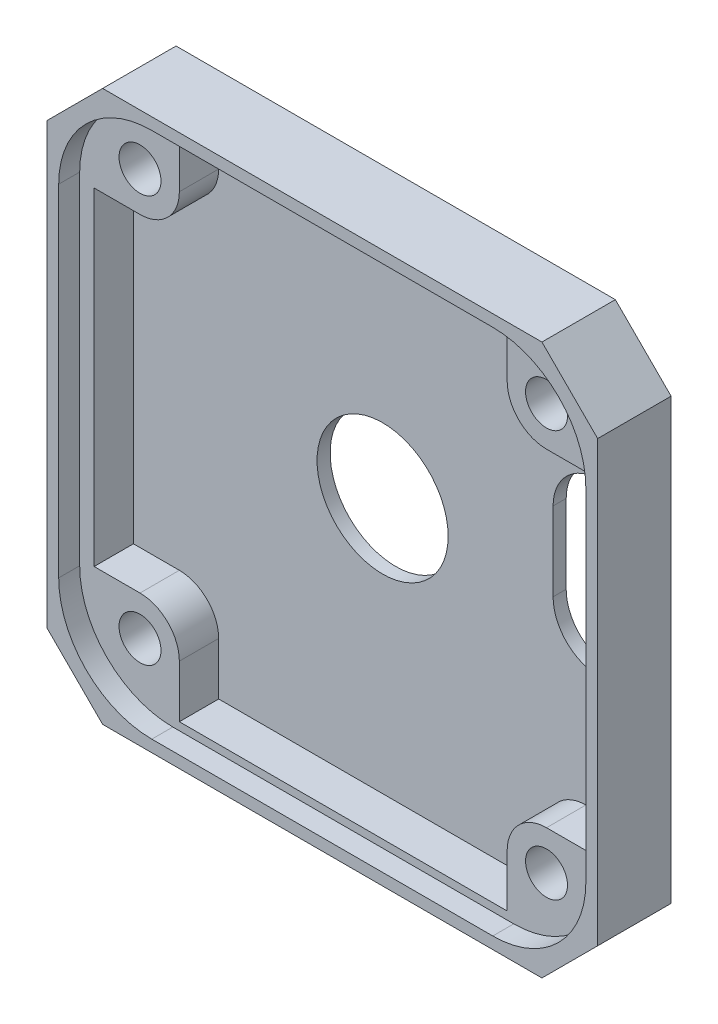
SolidWorks part; units mm, degrees
ref_plane "前视基准面" through (0, 0, 0) normal (0, 0, 1) x (1, 0, 0)
ref_plane "上视基准面" through (0, 0, 0) normal (0, 1, 0) x (1, 0, 0)
ref_plane "右视基准面" through (0, 0, 0) normal (1, 0, 0) x (0, 0, -1)
sketch "草图1" plane through (0, 0, 0) normal (0, 0, 1) x (1, 0, 0)
  line L0 (-21, 16.75) -> (-21, -16.75)
  line L1 (-16.75, 21) -> (16.75, 21)
  line L2 (-21, 16.75) -> (-16.75, 21)
  line L3 (21, 16.75) -> (21, -16.75)
  line L4 (-16.75, -21) -> (16.75, -21)
  line L5 (16.75, 21) -> (21, 16.75)
  line L6 (21, -16.75) -> (16.75, -21)
  line L7 (-21, -16.75) -> (-16.75, -21)
  line L12 (13, 6) -> (13, 0)
  line L15 (16.5, 9.5) -> (20, 9.5)
  line L16 (16.5, -3.5) -> (20, -3.5)
  line L17 (20, 9.5) -> (20, -3.5)
  circle A4 centre (0, 0) radius 5
  circle A7 centre (-15.5, 15.5) radius 1.6
  circle A8 centre (15.5, 15.5) radius 1.6
  circle A9 centre (-15.5, -15.5) radius 1.6
  circle A10 centre (15.5, -15.5) radius 1.6
  arc A11 (13, 0) -> (16.5, -3.5) centre (16.5, 0) ccw
  arc A12 (16.5, 9.5) -> (13, 6) centre (16.5, 6) ccw
extrude "凸台-拉伸3" add sketch "草图1" along normal blind 1
sketch "草图3" plane through (0, 0, 1) normal (0, 0, 1) x (1, 0, 0)
  line L0 (-16.75, 21) -> (-21, 16.75)
  line L1 (-21, 16.75) -> (-21, -16.75)
  line L2 (-21, -16.75) -> (-16.75, -21)
  line L3 (-16.75, -21) -> (16.75, -21)
  line L4 (16.75, -21) -> (21, -16.75)
  line L5 (21, -16.75) -> (21, 16.75)
  line L6 (21, 16.75) -> (16.75, 21)
  line L7 (16.75, 21) -> (-16.75, 21)
  line L8 (-12.5, 15.5) -> (-12.5, 19.5)
  line L9 (-15.5, 12.5) -> (-19, 12.5)
  line L10 (12.5, 15.5) -> (12.5, 19.5)
  line L11 (15.5, 12.5) -> (19, 12.5)
  line L12 (-15.5, -12.5) -> (-19, -12.5)
  line L13 (-12.5, -15.5) -> (-12.5, -19.5)
  line L14 (12.5, -15.5) -> (12.5, -19.5)
  line L15 (15.5, -12.5) -> (19, -12.5)
  line L16 (19, 12.5) -> (19, 9.5)
  line L17 (-19, 12.5) -> (-19, -12.5)
  line L18 (-12.5, -19.5) -> (12.5, -19.5)
  line L19 (-12.5, 19.5) -> (12.5, 19.5)
  line L20 (19, 9.5) -> (20, 9.5)
  line L21 (20, 9.5) -> (16.5, 9.5) construction
  line L22 (20, 9.5) -> (20, -3.5)
  line L23 (20, -3.5) -> (19, -3.5)
  line L24 (19, -3.5) -> (19, -12.5)
  arc A0 (-15.5, 12.5) -> (-12.5, 15.5) centre (-15.5, 15.5) ccw
  circle A1 centre (-15.5, 15.5) radius 1.6
  arc A2 (12.5, 15.5) -> (15.5, 12.5) centre (15.5, 15.5) ccw
  circle A3 centre (15.5, 15.5) radius 1.6
  arc A4 (-12.5, -15.5) -> (-15.5, -12.5) centre (-15.5, -15.5) ccw
  circle A5 centre (-15.5, -15.5) radius 1.6
  arc A6 (15.5, -12.5) -> (12.5, -15.5) centre (15.5, -15.5) ccw
  circle A7 centre (15.5, -15.5) radius 1.6
extrude "凸台-拉伸4" add sketch "草图3" along normal blind 3
sketch "草图4" plane through (0, 0, 4) normal (0, 0, 1) x (1, 0, 0)
  line L0 (-16.75, 21) -> (-21, 16.75)
  line L1 (-21, 16.75) -> (-21, -16.75)
  line L2 (-21, -16.75) -> (-16.75, -21)
  line L3 (-16.75, -21) -> (16.75, -21)
  line L4 (16.75, -21) -> (21, -16.75)
  line L5 (21, -16.75) -> (21, 16.75)
  line L6 (21, 16.75) -> (16.75, 21)
  line L7 (16.75, 21) -> (-16.75, 21)
  line L28 (-20.1, 13) -> (-20.1, -13)
  line L29 (-13, -20.1) -> (13, -20.1)
  line L30 (20.1, -13) -> (20.1, 13)
  line L31 (13, 20.1) -> (-13, 20.1)
  arc A20 (-13, 20.1) -> (-20.1, 13) centre (-13, 13) ccw
  arc A21 (-20.1, -13) -> (-13, -20.1) centre (-13, -13) ccw
  arc A22 (13, -20.1) -> (20.1, -13) centre (13, -13) ccw
  arc A23 (20.1, 13) -> (13, 20.1) centre (13, 13) ccw
extrude "凸台-拉伸5" add sketch "草图4" along normal blind 1.6
